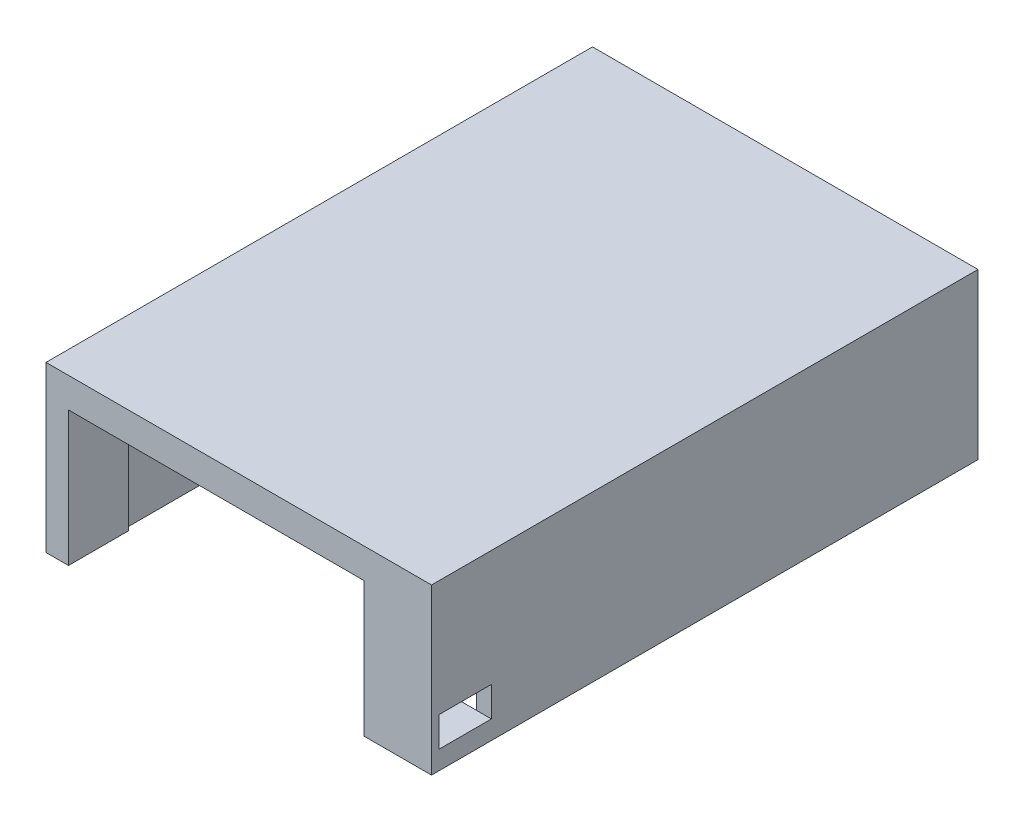
SolidWorks part; units mm, degrees
ref_plane "Front Plane" through (0, 0, 0) normal (0, 0, 1) x (1, 0, 0)
ref_plane "Top Plane" through (0, 0, 0) normal (0, 1, 0) x (1, 0, 0)
ref_plane "Right Plane" through (0, 0, 0) normal (1, 0, 0) x (0, 0, -1)
sketch "Sketch1" plane through (0, 0, 0) normal (0, 1, 0) x (1, 0, 0)
  line L1 (-61.3745, 37.3181) -> (-9.8745, 37.3181)
  line L2 (-61.3745, 37.3181) -> (-61.3745, -35.6819)
  line L3 (-61.3745, -35.6819) -> (-9.8745, -35.6819)
  line L4 (-9.8745, 37.3181) -> (-9.8745, -35.6819)
  dimension "D1" = 51.5
  dimension "D2" = 73
extrude "Boss-Extrude1" add sketch "Sketch1" along normal blind 22 contours L1 L4 L3 L2
sketch "Sketch2" plane through (0, 0, 0) normal (0, -1, 0) x (1, 0, 0)
  line L1 (-61.3745, -37.3181) -> (-61.3745, 35.6819) construction
  line L2 (-61.3745, 27.6819) -> (-58.3745, 27.6819)
  line L3 (-61.3745, 35.6819) -> (-9.8745, 35.6819) construction
  line L4 (-9.8745, -29.3181) -> (-12.8745, -29.3181)
  line L5 (-9.8745, -37.3181) -> (-9.8745, 35.6819) construction
  line L6 (-12.8745, -29.3181) -> (-12.8745, -37.3181)
  line L7 (-61.3745, -37.3181) -> (-9.8745, -37.3181) construction
  line L8 (-61.3745, -37.3181) -> (-52.3745, -37.3181)
  line L9 (-52.3745, -37.3181) -> (-52.3745, -29.3181)
  line L10 (-52.3745, -29.3181) -> (-61.3745, -29.3181)
  line L11 (-18.8745, 35.6819) -> (-18.8745, 27.6819)
  line L12 (-18.8745, 27.6819) -> (-9.8745, 27.6819)
  line L13 (-54.3745, 35.6819) -> (-18.8745, 35.6819)
  line L14 (-9.8745, -29.3181) -> (-9.8745, 27.6819)
  line L15 (-61.3745, -29.3181) -> (-61.3745, 27.6819)
  line L16 (-12.8745, -37.3181) -> (-52.3745, -37.3181)
  line L17 (-61.3745, 27.6819) -> (-61.3745, 35.6819)
  line L18 (-61.3745, -29.3181) -> (-58.8745, -29.3181)
  line L19 (-61.3745, -29.3181) -> (-61.3745, 27.6819)
  line L20 (-61.3745, 27.6819) -> (-58.8745, 27.6819)
  line L21 (-58.8745, -29.3181) -> (-58.8745, 27.6819)
  line L22 (-9.8745, 27.6819) -> (-11.8759, 27.6819)
  line L23 (-9.8745, 27.6819) -> (-9.8745, -29.3181)
  line L24 (-9.8745, -29.3181) -> (-11.8759, -29.3181)
  line L25 (-11.8759, 27.6819) -> (-11.8759, -29.3181)
  line L26 (-61.3745, 35.6819) -> (-58.3745, 35.6819)
  line L27 (-58.3745, 27.6819) -> (-58.3745, 35.6819)
  dimension "D1" = 3
  dimension "D3" = 8
  dimension "D4" = 3
  dimension "D5" = 9
  dimension "D6" = 8
  dimension "D7" = 9
  dimension "D8" = 8
  dimension "D9" = 2.5
extrude "Cut-Extrude1" cut sketch "Sketch2" against normal blind 18
sketch "Sketch4" plane through (0, 0, 0) normal (0, -1, 0) x (1, 0, 0)
  line L0 (-61.3745, -37.3181) -> (-61.3745, 35.6819) construction
  line L2 (-18.8745, 27.6819) -> (-11.8759, 27.6819) construction
  line L3 (-61.3745, -37.3181) -> (-52.3745, -37.3181) construction
  line L4 (-9.8745, -37.3181) -> (-9.8745, 35.6819) construction
  circle A0 centre (-15.8745, 31.6819) radius 2
  circle A1 centre (-55.3745, -33.3181) radius 2
  point P0 (-61.3745, -0.8181)
  dimension "D3" = 6
  dimension "D1" = 6
  dimension "D2" = 4
  dimension "D4" = 4
extrude "Cut-Extrude2" cut sketch "Sketch4" against normal blind 16
sketch "Sketch7" plane through (-61.3745, 0, 0) normal (-1, 0, 0) x (0, 0, 1)
  line L0 (-37.3181, 0) -> (35.6819, 0) construction
  line L1 (-36.3181, 6.5) -> (-29.3181, 6.5)
  line L2 (-36.3181, 6.5) -> (-36.3181, 2.5)
  line L3 (-36.3181, 2.5) -> (-29.3181, 2.5)
  line L4 (-29.3181, 6.5) -> (-29.3181, 2.5)
  line L5 (-37.3181, 22) -> (-37.3181, 0) construction
  dimension "D1" = 4
  dimension "D2" = 7
  dimension "D3" = 2.5
  dimension "D4" = 1
extrude "Cut-Extrude3" cut sketch "Sketch7" against normal blind 8.5
sketch "Sketch9" plane through (-9.8745, 0, 0) normal (1, 0, 0) x (0, 0, -1)
  line L0 (-35.6819, 22) -> (-35.6819, 0) construction
  line L1 (-34.6819, 6.5) -> (-27.6819, 6.5)
  line L2 (-34.6819, 6.5) -> (-34.6819, 2.5)
  line L3 (-34.6819, 2.5) -> (-27.6819, 2.5)
  line L4 (-27.6819, 6.5) -> (-27.6819, 2.5)
  line L5 (37.3181, 0) -> (-35.6819, 0) construction
  dimension "D1" = 7
  dimension "D2" = 4
  dimension "D3" = 1
  dimension "D4" = 2.5
extrude "Cut-Extrude4" cut sketch "Sketch9" against normal blind 8.5
